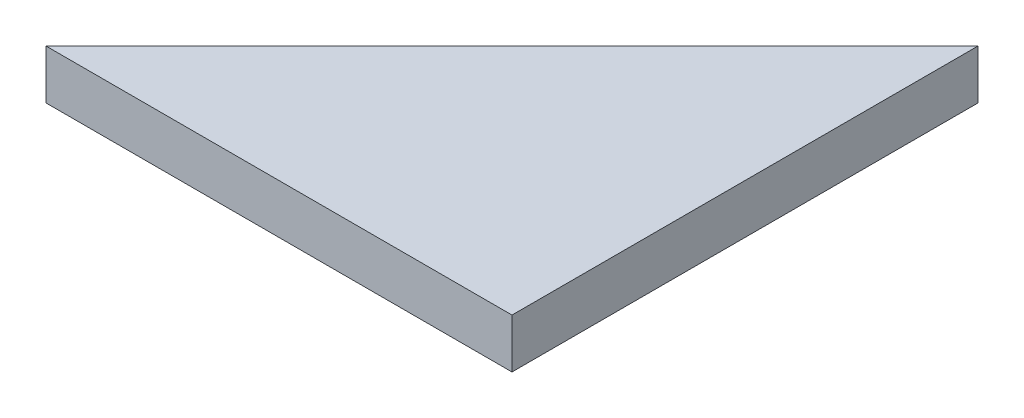
SolidWorks part; units mm, degrees
ref_plane "Plan de face" through (0, 0, 0) normal (0, 0, 1) x (1, 0, 0)
ref_plane "Plan de dessus" through (0, 0, 0) normal (0, 1, 0) x (1, 0, 0)
ref_plane "Plan de droite" through (0, 0, 0) normal (1, 0, 0) x (0, 0, -1)
sketch "Esquisse1" plane through (0, 0, 0) normal (0, 1, 0) x (1, 0, 0)
  line L0 (0, 60) -> (-60, 0)
  line L1 (-60, 0) -> (0, 0)
  line L2 (0, 0) -> (0, 60)
  line L3 (-34.0025, 0) -> (34.0025, 0) construction
  dimension "D1" = 60
extrude "Boss.-Extru.1" add sketch "Esquisse1" along normal blind 6.35
